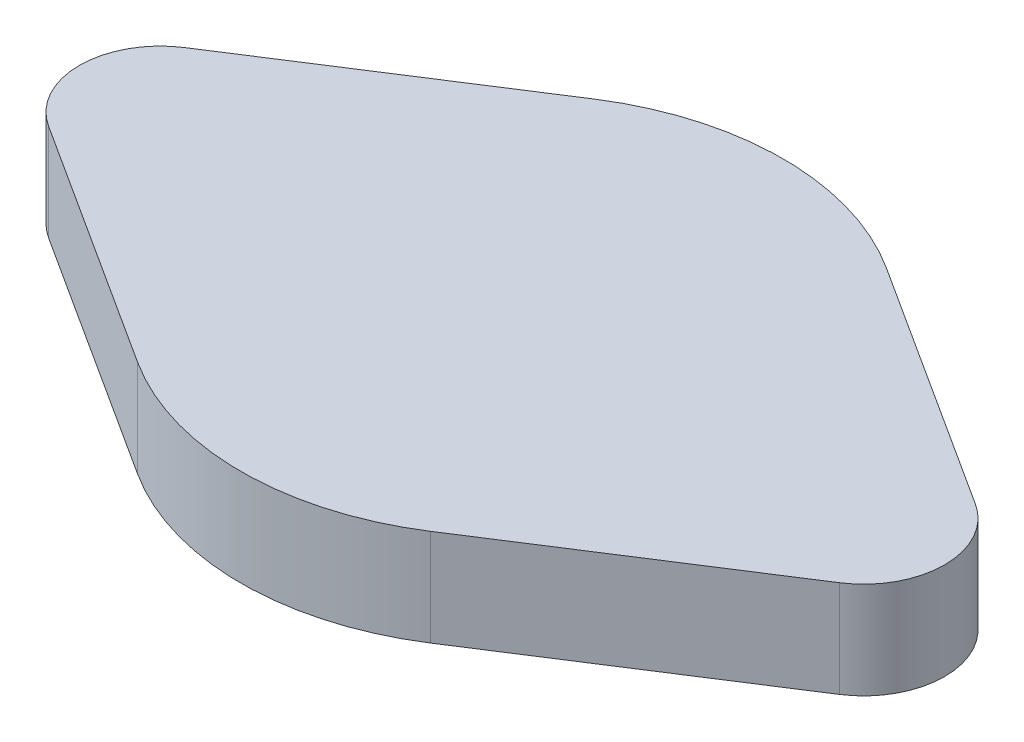
SolidWorks part; units mm, degrees
material "ABS"
ref_plane "Front Plane" through (0, 0, 0) normal (0, 0, 1) x (1, 0, 0)
ref_plane "Top Plane" through (0, 0, 0) normal (0, 1, 0) x (1, 0, 0)
ref_plane "Right Plane" through (0, 0, 0) normal (1, 0, 0) x (0, 0, -1)
sketch "Sketch1" plane through (0, 0, 0) normal (0, 1, 0) x (1, 0, 0)
  line L0 (18.1754, 0) -> (-18.1754, 0) construction
  line L2 (-20.4324, 3.5129) -> (-7.5676, 11.7784)
  line L3 (-21.3509, 0) -> (-19.7631, -2.75) construction
  line L4 (-19.7631, -2.75) -> (-16.5877, -2.75) construction
  line L5 (-16.5877, -2.75) -> (-15, 0) construction
  line L6 (-15, 0) -> (-16.5877, 2.75) construction
  line L7 (-16.5877, 2.75) -> (-19.7631, 2.75) construction
  line L8 (-19.7631, 2.75) -> (-21.3509, 0) construction
  line L9 (-20.4324, -3.5129) -> (-7.5676, -11.7784)
  line L10 (0, 0) -> (0, 14) construction
  line L11 (20.4324, -3.5129) -> (7.5676, -11.7784)
  line L12 (20.4324, 3.5129) -> (7.5676, 11.7784)
  circle A0 centre (0, 0) radius 8 construction
  circle A1 centre (0, 0) radius 4.1 construction
  arc A6 (-7.5676, -11.7784) -> (7.5676, -11.7784) centre (0, 0) ccw
  circle A7 centre (-18.1754, 0) radius 1.6 construction
  circle A8 centre (18.1754, 0) radius 1.6 construction
  circle A9 centre (-18.1754, 0) radius 2.75 construction
  arc A10 (-20.4324, 3.5129) -> (-20.4324, -3.5129) centre (-18.1754, 0) ccw
  arc A11 (20.4324, 3.5129) -> (20.4324, -3.5129) centre (18.1754, 0) cw
  arc A12 (7.5676, 11.7784) -> (-7.5676, 11.7784) centre (0, 0) ccw
  circle A13 centre (0, 8) radius 1.6 construction
  circle A14 centre (8, 0) radius 1.6 construction
  circle A15 centre (0, -8) radius 1.6 construction
  circle A16 centre (-8, 0) radius 1.6 construction
  point P9 (0, 0)
  point P16 (0, 0)
  dimension "D1" = 16
  dimension "D2" = 8.2
  dimension "D4" = 3.2
  dimension "D6" = 28
  dimension "D7" = 3.2
  dimension "D9" = 15
  dimension "D8" = 5.5
extrude "Boss-Extrude1" add sketch "Sketch1" along normal blind 5
